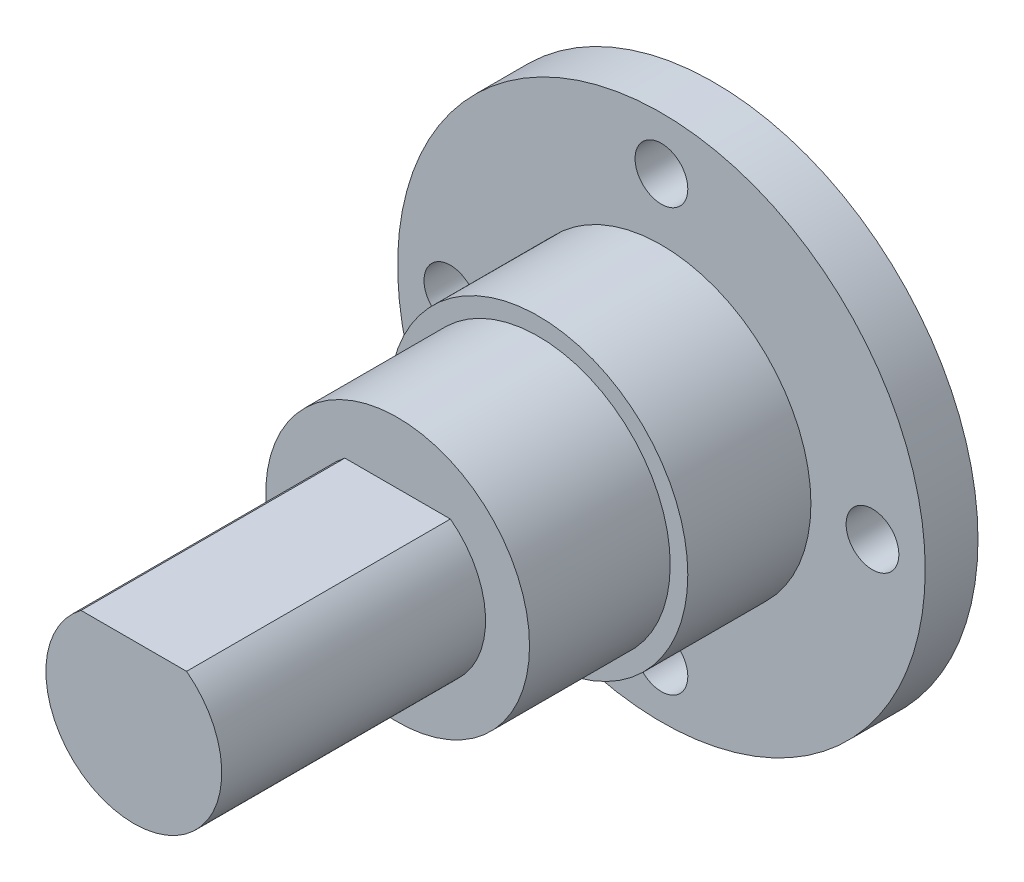
SolidWorks part; units mm, degrees
ref_plane "前视基准面" through (0, 0, 0) normal (0, 0, 1) x (1, 0, 0)
ref_plane "上视基准面" through (0, 0, 0) normal (0, 1, 0) x (1, 0, 0)
ref_plane "右视基准面" through (0, 0, 0) normal (1, 0, 0) x (0, 0, -1)
sketch "草图1" plane through (0, 0, 0) normal (0, 0, 1) x (1, 0, 0)
  circle A0 centre (0, 0) radius 15
extrude "凸台-拉伸1" add sketch "草图1" along normal blind 3
sketch "草图2" plane through (0, 0, 3) normal (0, 0, 1) x (1, 0, 0)
  circle A0 centre (0, 0) radius 12 construction
  circle A1 centre (0, 12) radius 1.5
  circle A2 centre (12, 0) radius 1.5
  circle A3 centre (0, -12) radius 1.5
  circle A4 centre (-12, 0) radius 1.5
  point P14 (0, 0)
  dimension "D1" = 4
extrude "切除-拉伸1" cut sketch "草图2" against normal through all
sketch "草图5" plane through (0, 0, 3) normal (0, 0, 1) x (1, 0, 0)
  circle A0 centre (0, 0) radius 5
extrude "凸台-拉伸2" add sketch "草图5" along normal blind 30
sketch "草图7" plane through (0, 0, 3) normal (0, 0, 1) x (1, 0, 0)
  circle A0 centre (0, 0) radius 7.5
extrude "凸台-拉伸4" add sketch "草图7" along normal blind 15
sketch "草图8" plane through (0, 0, 33) normal (0, 0, 1) x (1, 0, 0)
  line L0 (0, 0) -> (0, 4) construction
  line L1 (-3, 4) -> (3, 4)
  arc A0 (3, 4) -> (-3, 4) centre (0, 0) ccw
extrude "切除-拉伸2" cut sketch "草图8" against normal up to surface (15 mm away) up to face at (5, 0, 18)
sketch "草图9" plane through (0, 0, 3) normal (0, 0, 1) x (1, 0, 0)
  circle A0 centre (0, 0) radius 8.5
extrude "凸台-拉伸5" add sketch "草图9" along normal blind 7
